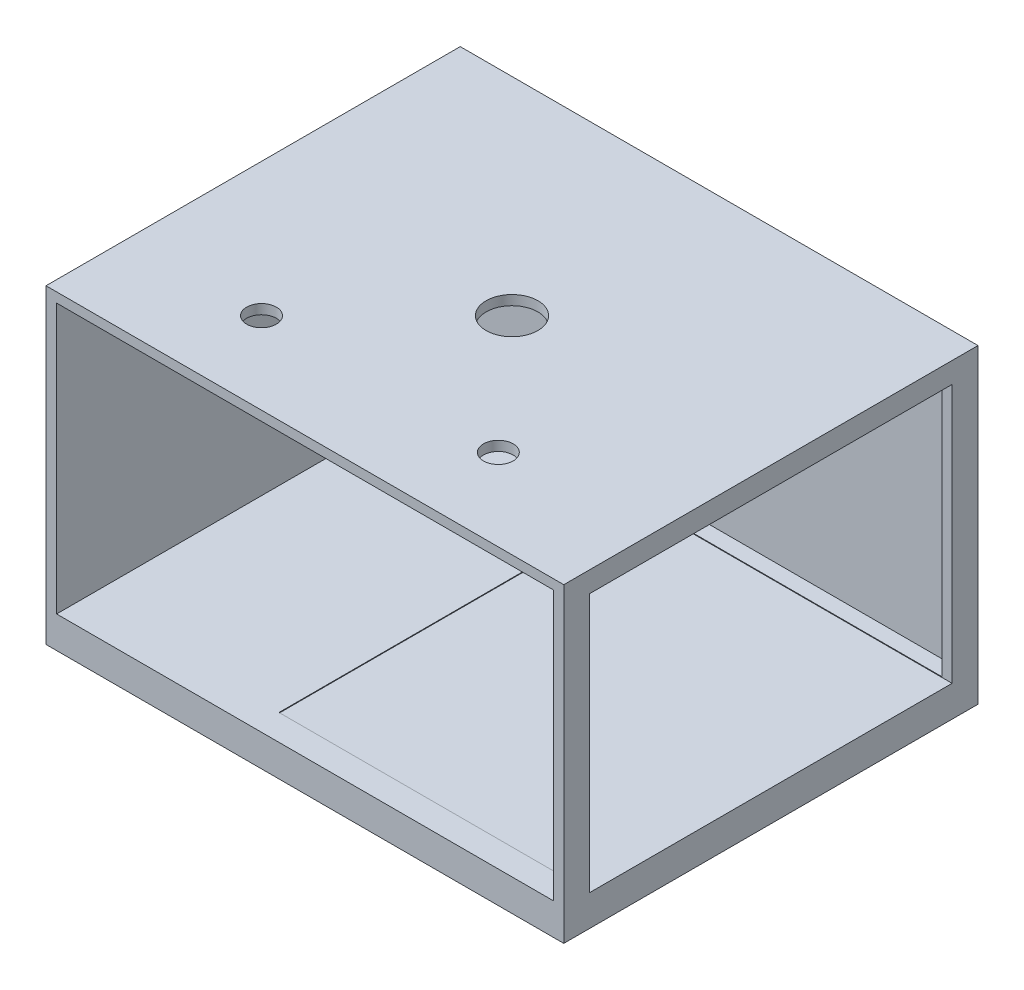
SolidWorks part; units mm, degrees
ref_plane "Front Plane" through (0, 0, 0) normal (0, 0, 1) x (1, 0, 0)
ref_plane "Top Plane" through (0, 0, 0) normal (0, 1, 0) x (1, 0, 0)
ref_plane "Right Plane" through (0, 0, 0) normal (1, 0, 0) x (0, 0, -1)
sketch "Sketch1" plane through (0, 0, 0) normal (0, 1, 0) x (1, 0, 0)
  line L1 (-250, 200) -> (250, 200)
  line L2 (-250, 200) -> (-250, -200)
  line L3 (-250, -200) -> (250, -200)
  line L4 (250, 200) -> (250, -200)
  line L5 (-250, 200) -> (250, -200) construction
  line L6 (-250, -200) -> (250, 200) construction
  point P0 (0, 0)
  dimension "D1" = 500
  dimension "D2" = 400
extrude "Boss-Extrude1" add sketch "Sketch1" along normal blind 300
sketch "Sketch2" plane through (0, 0, 200) normal (0, 0, 1) x (1, 0, 0)
  line L1 (-239.7389, 290.6321) -> (240.2611, 290.6321)
  line L2 (-239.7389, 290.6321) -> (-239.7389, 30.6321)
  line L3 (-239.7389, 30.6321) -> (240.2611, 30.6321)
  line L4 (240.2611, 290.6321) -> (240.2611, 30.6321)
  line L5 (-239.7389, 290.6321) -> (240.2611, 30.6321) construction
  line L6 (-239.7389, 30.6321) -> (240.2611, 290.6321) construction
  point P0 (0.2611, 160.6321)
  dimension "D1" = 480
  dimension "D2" = 260
extrude "Cut-Extrude1" cut sketch "Sketch2" against normal blind 390
sketch "Sketch3" plane through (250, 0, 0) normal (1, 0, 0) x (0, 0, -1)
  line L0 (-200, 300) -> (200, 300) construction
  line L1 (-175, 280) -> (175, 280)
  line L2 (-175, 280) -> (-175, 30)
  line L3 (-175, 30) -> (175, 30)
  line L4 (175, 280) -> (175, 30)
  line L5 (-175, 280) -> (175, 30) construction
  line L6 (-175, 30) -> (175, 280) construction
  point P0 (0, 155)
  point P5 (0, 0)
  dimension "D1" = 350
  dimension "D2" = 250
  dimension "D3" = 20
extrude "Cut-Extrude2" cut sketch "Sketch3" against normal blind 300
sketch "Sketch4" plane through (0, 300, 0) normal (0, 1, 0) x (1, 0, 0)
  circle A0 centre (0, 0) radius 25
  dimension "D1" = 50
extrude "Cut-Extrude3" cut sketch "Sketch4" against normal blind 210
sketch "Sketch5" plane through (0, 300, 0) normal (0, 1, 0) x (1, 0, 0)
  circle A0 centre (-120.9475, -120.9475) radius 14.3303
  circle A1 centre (107.7636, -120.9475) radius 14.3303
extrude "Cut-Extrude4" cut sketch "Sketch5" against normal blind 210
